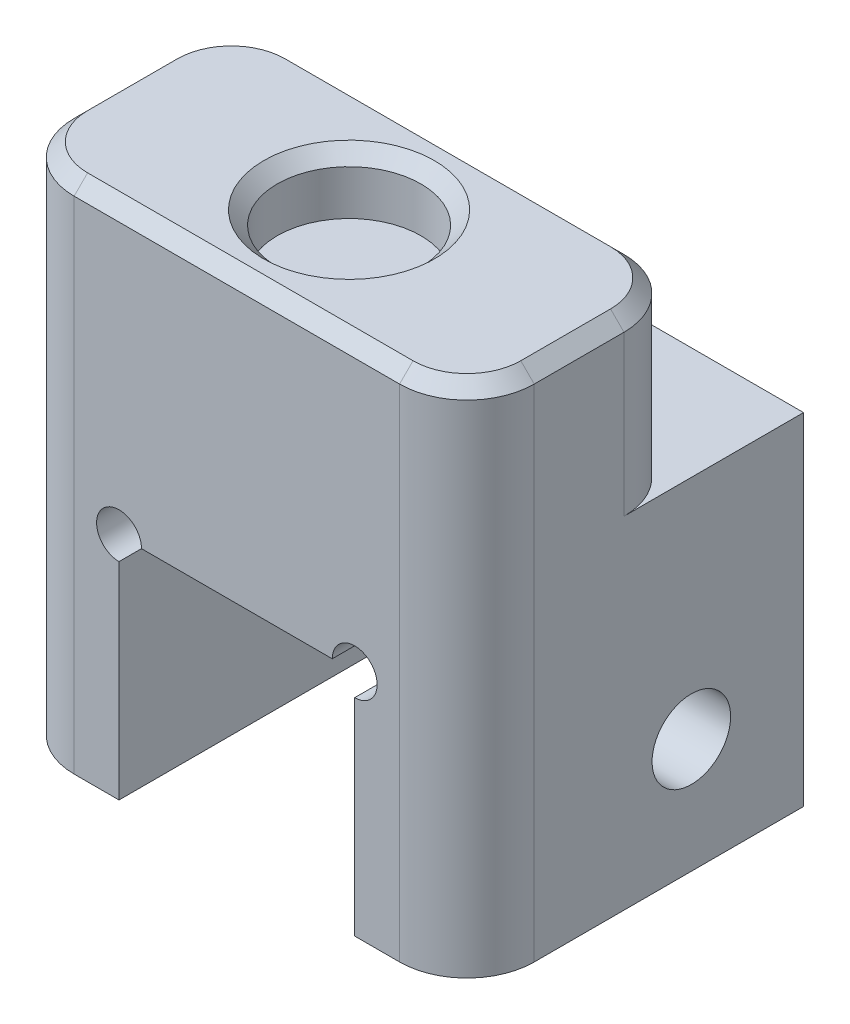
SolidWorks part; units mm, degrees
material "ﾎﾟﾘｴｽﾃﾙ樹脂"
ref_plane "正面" through (0, 0, 0) normal (0, 0, 1) x (1, 0, 0)
ref_plane "平面" through (0, 0, 0) normal (0, 1, 0) x (1, 0, 0)
ref_plane "右側面" through (0, 0, 0) normal (1, 0, 0) x (0, 0, -1)
sketch "ｽｹｯﾁ1" plane through (0, 0, 0) normal (0, 0, 1) x (1, 0, 0)
  line L0 (0, 11.45) -> (0, -11.45) construction
  line L1 (-10.25, -11.45) -> (10.25, -11.45)
  line L2 (-10.25, -11.45) -> (-10.25, 11.45)
  line L3 (-10.25, 11.45) -> (10.25, 11.45)
  line L4 (10.25, -11.45) -> (10.25, 11.45)
  line L5 (-10.25, -11.45) -> (10.25, 11.45) construction
  line L6 (-10.25, 11.45) -> (10.25, -11.45) construction
  line L8 (-5.25, -1.25) -> (5.25, -1.25)
  line L9 (-5.25, -1.25) -> (-5.25, -11.45)
  line L10 (-5.25, -11.45) -> (5.25, -11.45)
  line L11 (5.25, -1.25) -> (5.25, -11.45)
  line L12 (-5.25, -1.25) -> (5.25, -11.45) construction
  line L13 (-5.25, -11.45) -> (5.25, -1.25) construction
  point P0 (0, 0)
  point P7 (0, -6.35)
  dimension "D1" = 10.2
  dimension "D2" = 5
  dimension "D3" = 12.7
  dimension "D4" = 10.5
extrude "ﾎﾞｽ - 押し出し1" add sketch "ｽｹｯﾁ1" along normal blind 10 contours L8 L11 L1 L4 L3 L2 L9
sketch "ｽｹｯﾁ5" plane through (0, 0, 0) normal (0, 0, -1) x (-1, 0, 0)
  line L0 (-10.25, 3.75) -> (10.25, 3.75)
  line L1 (-10.25, -11.45) -> (-10.25, 11.45) construction
  line L2 (10.25, -11.45) -> (10.25, 11.45) construction
  line L3 (10.25, 3.75) -> (10.25, -11.45)
  line L4 (10.25, -11.45) -> (5.25, -11.45)
  line L5 (5.25, -11.45) -> (5.25, -1.25)
  line L6 (5.25, -1.25) -> (-5.25, -1.25)
  line L7 (-5.25, -1.25) -> (-5.25, -11.45)
  line L8 (-5.25, -11.45) -> (-10.25, -11.45)
  line L9 (-10.25, -11.45) -> (-10.25, 3.75)
  dimension "D1" = 5
extrude "ﾎﾞｽ - 押し出し2" add sketch "ｽｹｯﾁ5" along normal blind 5
sketch "ｽｹｯﾁ2" plane through (0, 11.45, 0) normal (0, 1, 0) x (1, 0, 0)
  line L0 (0, 0) -> (0, -10) construction
  line L1 (-10.25, -10) -> (10.25, -10) construction
  circle A0 centre (0, -5) radius 3.2
  dimension "D1" = 6.4
extrude "ｶｯﾄ - 押し出し1" cut sketch "ｽｹｯﾁ2" against normal blind 2.6
sketch "ｽｹｯﾁ4" plane through (0, 0, 10) normal (0, 0, 1) x (1, 0, 0)
  circle A0 centre (5.25, -1.25) radius 1
  circle A1 centre (-5.25, -1.25) radius 1
  dimension "D1" = 2
extrude "ｶｯﾄ - 押し出し3" cut sketch "ｽｹｯﾁ4" against normal through all
sketch "ｽｹｯﾁ6" plane through (10.25, 0, 0) normal (1, 0, 0) x (0, 0, -1)
  line L0 (0, -11.45) -> (0, 3.75) construction
  line L1 (-10, -11.45) -> (5, -11.45) construction
  line L2 (5, 3.75) -> (0, 3.75) construction
  line L3 (5, 3.75) -> (5, -11.45) construction
  circle A0 centre (0, -6.35) radius 1.75
  dimension "D2" = 5.1
  dimension "D3" = 3.5
  dimension "D1" = 5
extrude "ｶｯﾄ - 押し出し4" cut sketch "ｽｹｯﾁ6" against normal through all
fillet "ﾌｨﾚｯﾄ1" radius 3 4 edges at (-10.25, 7.6, 0) (-10.25, 0, 10) (10.25, 7.6, 0) (10.25, 0, 10)
chamfer "面取り1" distance 0.6 angle 45 9 edges at (9.3713, 11.45, 0.8787) (10.25, 11.45, 5) (9.3713, 11.45, 9.1213) (0, 11.45, 10) (-9.3713, 11.45, 9.1213) (-10.25, 11.45, 5) (-9.3713, 11.45, 0.8787) (0, 11.45, 0) (-3.2, 11.45, 5)
